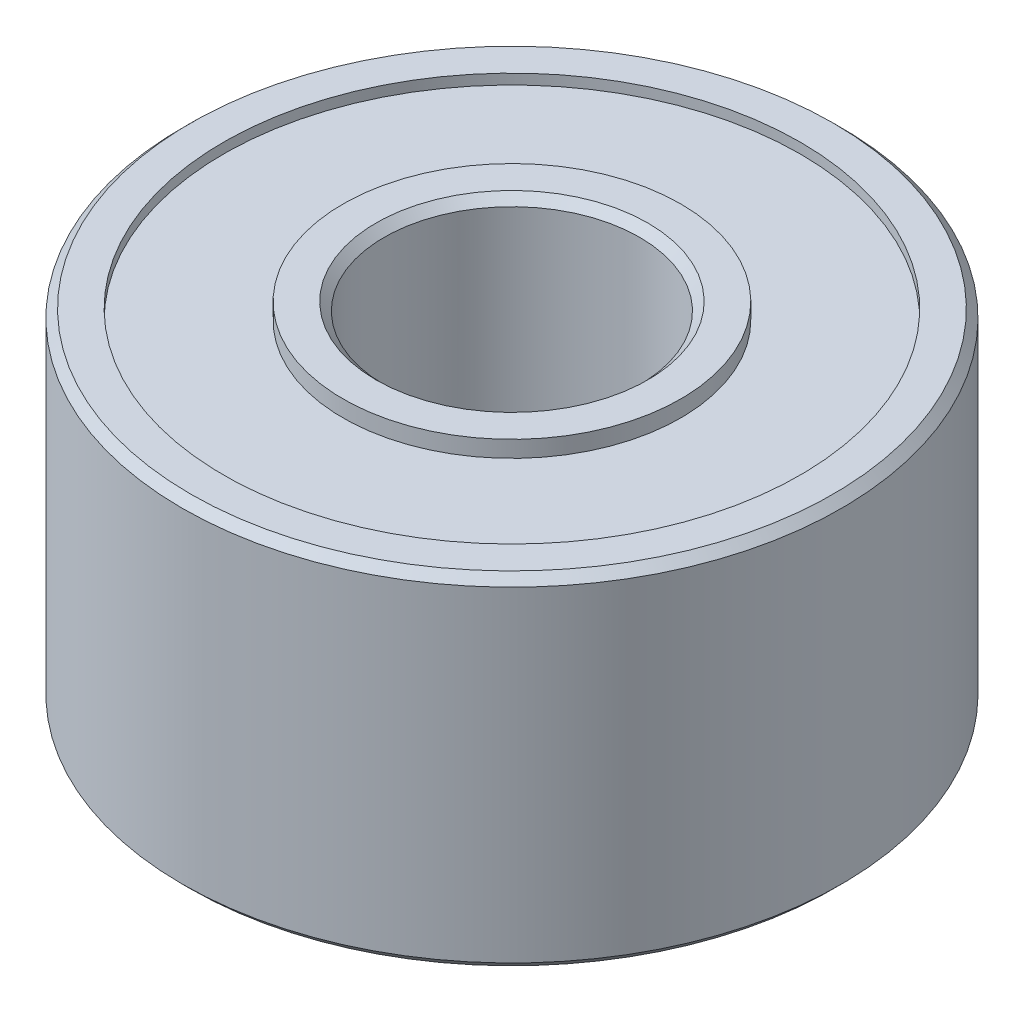
SolidWorks part; units mm, degrees
ref_plane "Front Plane" through (0, 0, 0) normal (0, 0, 1) x (1, 0, 0)
ref_plane "Top Plane" through (0, 0, 0) normal (0, 1, 0) x (1, 0, 0)
ref_plane "Right Plane" through (0, 0, 0) normal (1, 0, 0) x (0, 0, -1)
sketch "Sketch2" plane through (0, 0, 0) normal (0, 0, 1) x (1, 0, 0)
  line L12 (5.0269, 0) -> (0, 0) construction
  line L13 (1.55, 2.15) -> (1.55, -2.15)
  line L15 (4, -2.075) -> (4, 2.075) construction
  line L17 (1.55, -2.15) -> (1.55, 2.15) construction
  line L20 (1.55, -2.15) -> (2.05, -2.15)
  line L21 (2.05, -2.15) -> (2.05, -1.95)
  line L22 (2.05, -1.95) -> (3.5, -1.95)
  line L23 (3.5, -1.95) -> (3.5, -2.075)
  line L24 (3.5, -2.075) -> (4, -2.075)
  line L25 (4, -2.075) -> (4, 2.075)
  line L26 (4, 2.075) -> (3.5, 2.075)
  line L27 (3.5, 2.075) -> (3.5, 1.95)
  line L28 (3.5, 1.95) -> (2.05, 1.95)
  line L29 (2.05, 1.95) -> (2.05, 2.15)
  line L30 (2.05, 2.15) -> (1.55, 2.15)
  line L31 (0, -2) -> (0, 2.4102) construction
  line L32 (4, 2.075) -> (1.55, -2.075) construction
  line L33 (4, -2.075) -> (1.55, 2.075) construction
  point P0 (2.775, 0)
  dimension "D1" = 1.55
  dimension "D2" = 4
  dimension "D3" = 4.15
  dimension "D4" = 0.5
  dimension "D5" = 0.5
  dimension "D6" = 0.125
  dimension "D7" = 4.3
revolve "Revolve1" add sketch "Sketch2" angle 360 about L31
chamfer "Chamfer1" distance 0.1 angle 45 4 edges at (0, -2.15, -1.55) (0, -2.075, -4) (0, 2.15, -1.55) (0, 2.075, -4)
